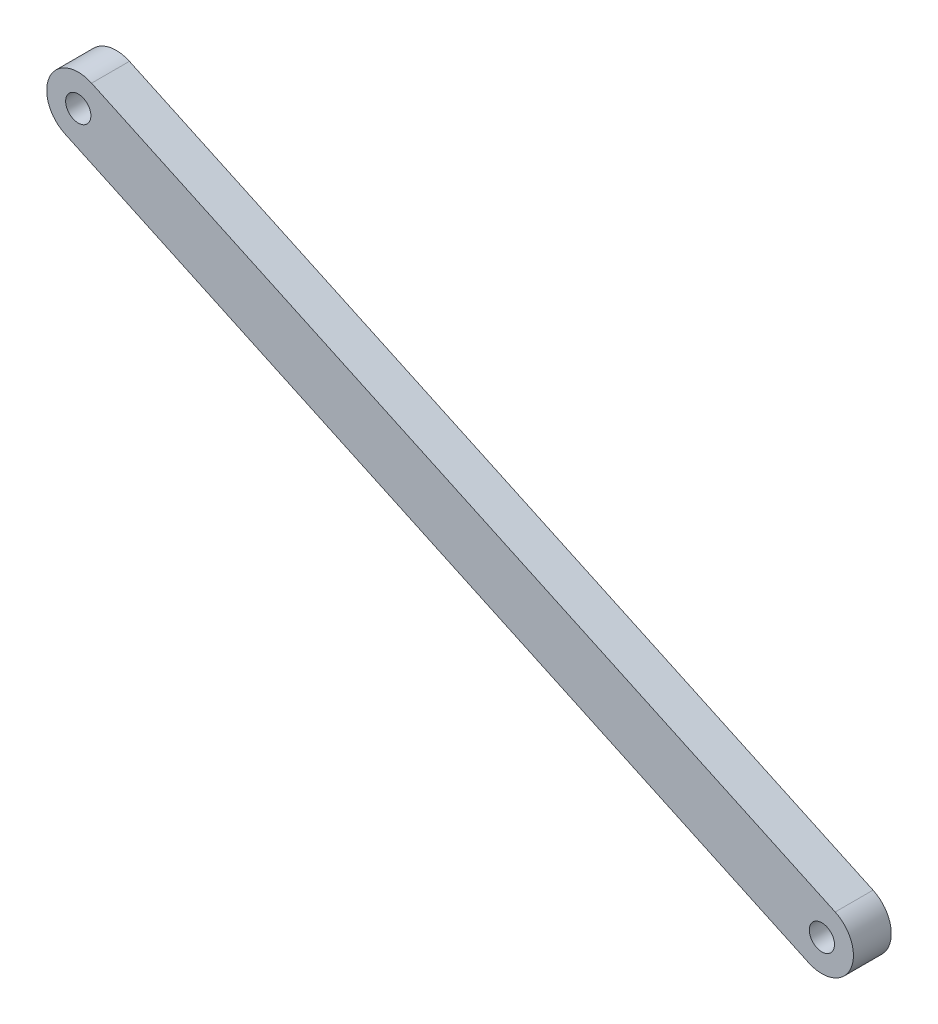
SolidWorks part; units mm, degrees
ref_plane "Спереди" through (0, 0, 0) normal (0, 0, 1) x (1, 0, 0)
ref_plane "Сверху" through (0, 0, 0) normal (0, 1, 0) x (1, 0, 0)
ref_plane "Справа" through (0, 0, 0) normal (1, 0, 0) x (0, 0, -1)
sketch "Sketch1" plane through (0, 0, 0) normal (0, 0, 1) x (1, 0, 0)
  line L0 (12.2142, 44.0917) -> (10.6042, 45.6329) construction
  line L5 (10.6042, 45.6329) -> (8.8374, 47.2581) construction
  line L6 (8.8374, 47.2581) -> (6.9022, 48.9738) construction
  line L7 (6.9022, 48.9738) -> (4.7865, 50.7872) construction
  line L8 (-20.6555, 56.1799) -> (38.2787, 28.7616) construction
  line L9 (-19.601, 58.4466) -> (39.3332, 31.0283)
  line L10 (-21.7101, 53.9132) -> (37.2241, 26.4949)
  line L33 (38.2787, 28.7616) -> (-20.6555, 56.1799) construction
  circle A0 centre (-20.6555, 56.1799) radius 1
  circle A2 centre (38.2787, 28.7616) radius 1
  arc A3 (-19.601, 58.4466) -> (-21.7101, 53.9132) centre (-20.6555, 56.1799) ccw
  arc A4 (37.2241, 26.4949) -> (39.3332, 31.0283) centre (38.2787, 28.7616) ccw
  spline S0 degree 4 poles (12.2142, 44.0917) (10.6042, 45.6329) (8.8374, 47.2581) (6.9022, 48.9738) (4.7865, 50.7872) knots 0 0 0 0 0 1 1 1 1 1 construction
  point P1 (8.8116, 42.4707)
  dimension "D6" = 2
  dimension "D1" = 5
  dimension "D2" = 65
  dimension "D7" = 10
extrude "Boss-Extrude1" add sketch "Sketch1" along normal blind 3
ref_plane "Plane1" through (17.811, 38.2839, 0) normal (0.4218, 0.9067, 0) x (0.9067, -0.4218, 0)
